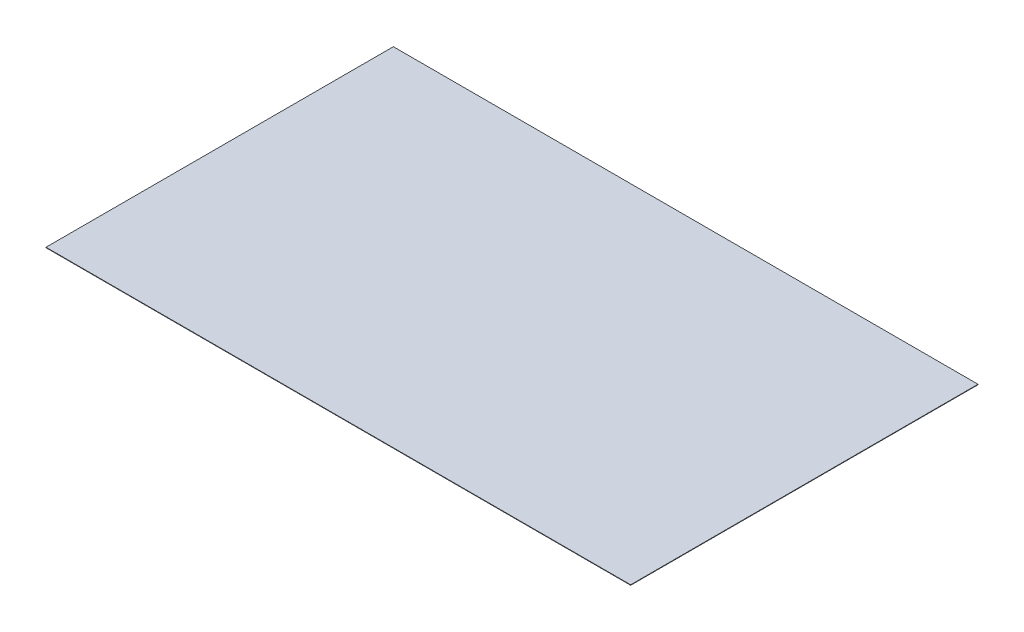
SolidWorks part; units mm, degrees
ref_plane "Front Plane" through (0, 0, 0) normal (0, 0, 1) x (1, 0, 0)
ref_plane "Top Plane" through (0, 0, 0) normal (0, 1, 0) x (1, 0, 0)
ref_plane "Right Plane" through (0, 0, 0) normal (1, 0, 0) x (0, 0, -1)
other "Configuration Table"
sketch "Sketch1" plane through (0, 0, 0) normal (0, 0, 1) x (1, 0, 0)
  line L1 (62.5, 690) -> (1337.5, 690)
  line L2 (62.5, 690) -> (62.5, 691)
  line L3 (62.5, 691) -> (1337.5, 691)
  line L4 (1337.5, 690) -> (1337.5, 691)
extrude "STORE_ayirici_sac_alt_1" add sketch "Sketch1" against normal blind 757.5 separate body
